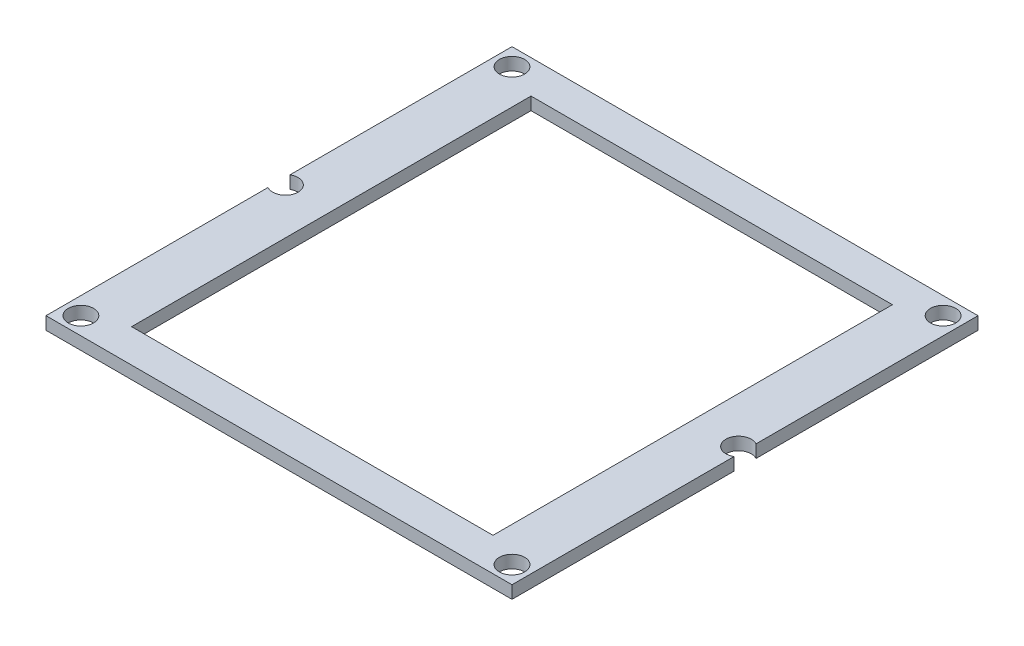
SolidWorks part; units mm, degrees
ref_plane "Front Plane" through (0, 0, 0) normal (0, 0, 1) x (1, 0, 0)
ref_plane "Top Plane" through (0, 0, 0) normal (0, 1, 0) x (1, 0, 0)
ref_plane "Right Plane" through (0, 0, 0) normal (1, 0, 0) x (0, 0, -1)
sketch "Sketch1" plane through (0, 0, 0) normal (0, 1, 0) x (1, 0, 0)
  line L0 (147, 147) -> (147, -147)
  line L1 (-147, -147) -> (147, -147)
  line L2 (-147, -147) -> (-147, 147)
  line L3 (-147, 147) -> (147, 147)
  line L5 (-147, -147) -> (147, 147) construction
  line L6 (-147, 147) -> (147, -147) construction
  line L7 (-114, -126) -> (114, -126)
  line L8 (-114, -126) -> (-114, 126)
  line L9 (-114, 126) -> (114, 126)
  line L10 (114, -126) -> (114, 126)
  line L11 (-114, -126) -> (114, 126) construction
  line L12 (-114, 126) -> (114, -126) construction
  point P0 (0, 0)
  point P5 (0, 0)
  dimension "D1" = 294
  dimension "D2" = 228
  dimension "D3" = 252
extrude "Boss-Extrude1" add sketch "Sketch1" along normal blind 8
sketch "Sketch2" plane through (0, 0, 0) normal (0, 1, 0) x (1, 0, 0)
  line L1 (147, 147) -> (-147, 147) construction
  line L2 (147, -147) -> (147, 147) construction
  circle A0 centre (136, 136) radius 8
  dimension "D1" = 16
  dimension "D2" = 11
  dimension "D3" = 11
extrude "Cut-Extrude1" cut sketch "Sketch2" along normal through all
sketch "Sketch4" plane through (0, 8, 0) normal (0, 1, 0) x (1, 0, 0)
  line L0 (136, -864) -> (136, 49136) construction
  circle A0 centre (142.94, 0) radius 8
  dimension "D1" = 6.94
  dimension "D2" = 16
mirror "Mirror2" about plane through (0, 0, 0) normal (0, 0, 1) of "Cut-Extrude1"
extrude "Cut-Extrude2" cut sketch "Sketch4" against normal through all
mirror "Mirror3" about plane through (0, 0, 0) normal (1, 0, 0) of "Cut-Extrude1", "Mirror2", "Cut-Extrude2"
